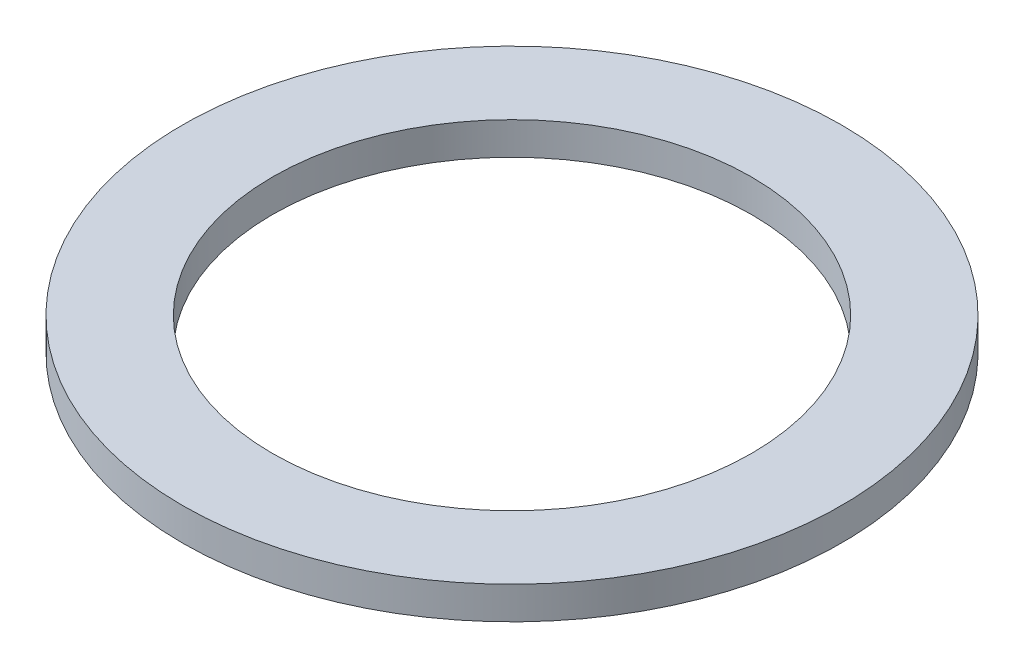
SolidWorks part; units mm, degrees
ref_plane "Front Plane" through (0, 0, 0) normal (0, 0, 1) x (1, 0, 0)
ref_plane "Top Plane" through (0, 0, 0) normal (0, 1, 0) x (1, 0, 0)
ref_plane "Right Plane" through (0, 0, 0) normal (1, 0, 0) x (0, 0, -1)
sketch "Sketch1" plane through (0, 0, 0) normal (0, 1, 0) x (1, 0, 0)
  circle A0 centre (0, 0) radius 8.7376
  dimension "OD" = 17.4752
extrude "Boss-Extrude1" add sketch "Sketch1" along normal blind 0.8636
sketch "Sketch5" plane through (0, 0.8636, 0) normal (0, 1, 0) x (-1, 0, 0)
  circle A0 centre (0, 0) radius 6.35
  dimension "ID" = 12.7
extrude "Cut-Extrude1" cut sketch "Sketch5" against normal through all
